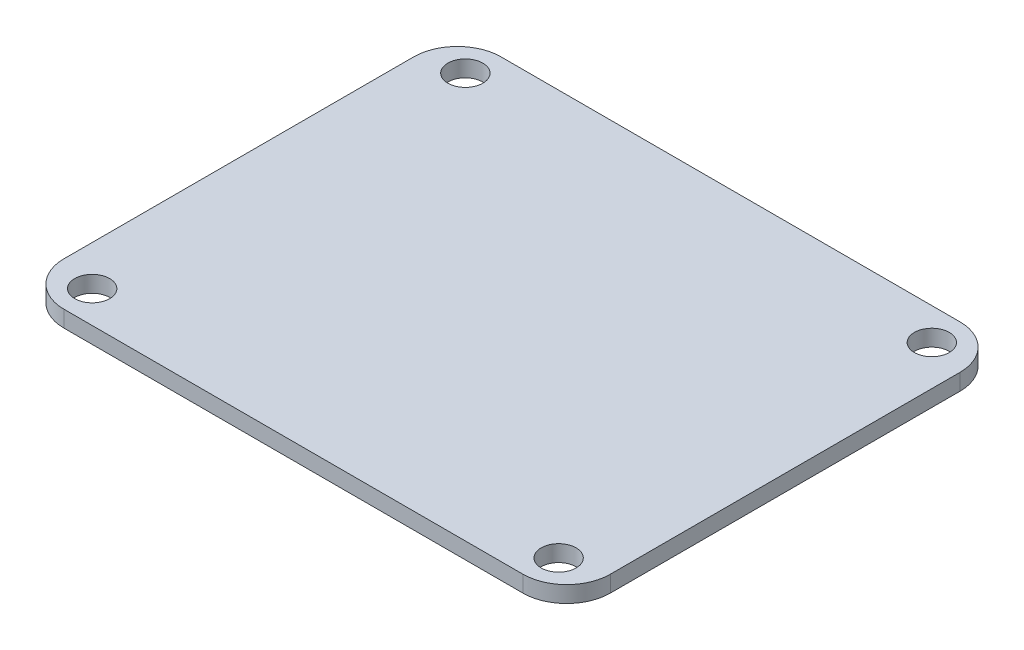
SolidWorks part; units mm, degrees
ref_plane "Спереди" through (0, 0, 0) normal (0, 0, 1) x (1, 0, 0)
ref_plane "Сверху" through (0, 0, 0) normal (0, 1, 0) x (1, 0, 0)
ref_plane "Справа" through (0, 0, 0) normal (1, 0, 0) x (0, 0, -1)
sketch "Эскиз1" plane through (0, 0, 0) normal (0, 1, 0) x (1, 0, 0)
  line L0 (5, 20) -> (5, -20) construction
  line L1 (-16, -20) -> (26, -20)
  line L2 (-20, -16) -> (-20, 16)
  line L3 (-16, 20) -> (26, 20)
  line L4 (30, -16) -> (30, 16)
  line L5 (-20, -20) -> (30, 20) construction
  line L6 (-20, 20) -> (30, -20) construction
  line L7 (5, 0) -> (-20, 0) construction
  line L8 (5, 0) -> (30, 0) construction
  arc A0 (-20, -16) -> (-16, -20) centre (-16, -16) ccw
  arc A1 (26, -20) -> (30, -16) centre (26, -16) ccw
  arc A2 (30, 16) -> (26, 20) centre (26, 16) ccw
  arc A3 (-16, 20) -> (-20, 16) centre (-16, 16) ccw
  circle A4 centre (-16.3438, 17.075) radius 1.5976
  circle A5 centre (26.3438, -17.075) radius 1.5976
  circle A6 centre (26.3438, 17.075) radius 1.5976
  circle A7 centre (-16.3438, -17.075) radius 1.5976
  dimension "D1" = 4
extrude "Бобышка-Вытянуть1" add sketch "Эскиз1" along normal blind 1.5
